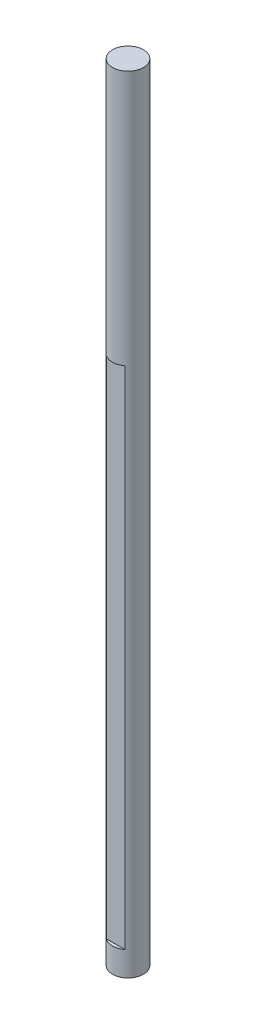
SolidWorks part; units mm, degrees
ref_plane "Front Plane" through (0, 0, 0) normal (0, 0, 1) x (1, 0, 0)
ref_plane "Top Plane" through (0, 0, 0) normal (0, 1, 0) x (1, 0, 0)
ref_plane "Right Plane" through (0, 0, 0) normal (1, 0, 0) x (0, 0, -1)
sketch "Sketch1" plane through (0, 0, 0) normal (0, 1, 0) x (1, 0, 0)
  circle A0 centre (0, 0) radius 4
  dimension "D1" = 8
extrude "Boss-Extrude1" add sketch "Sketch1" along normal blind 203.2
sketch "Sketch2" plane through (0, 0, 0) normal (0, -1, 0) x (1, 0, 0)
  circle A0 centre (0, 0) radius 1.865
extrude "Cut-Extrude1" cut sketch "Sketch2" against normal blind 12.7 contours A0
sketch "Sketch4" plane through (0, 0, 0) normal (0, -1, 0) x (1, 0, 0)
  line L0 (-2.421, 3.1841) -> (2.421, 3.1841)
  circle A0 centre (0, 0) radius 4 construction
  circle A1 centre (0, 0) radius 4
  circle M3 centre (0, 0) radius 4
extrude "Cut-Extrude2" cut sketch "Sketch4" against normal blind 130.81 from offset 6.35 contours L0 M3 offset against normal yes
